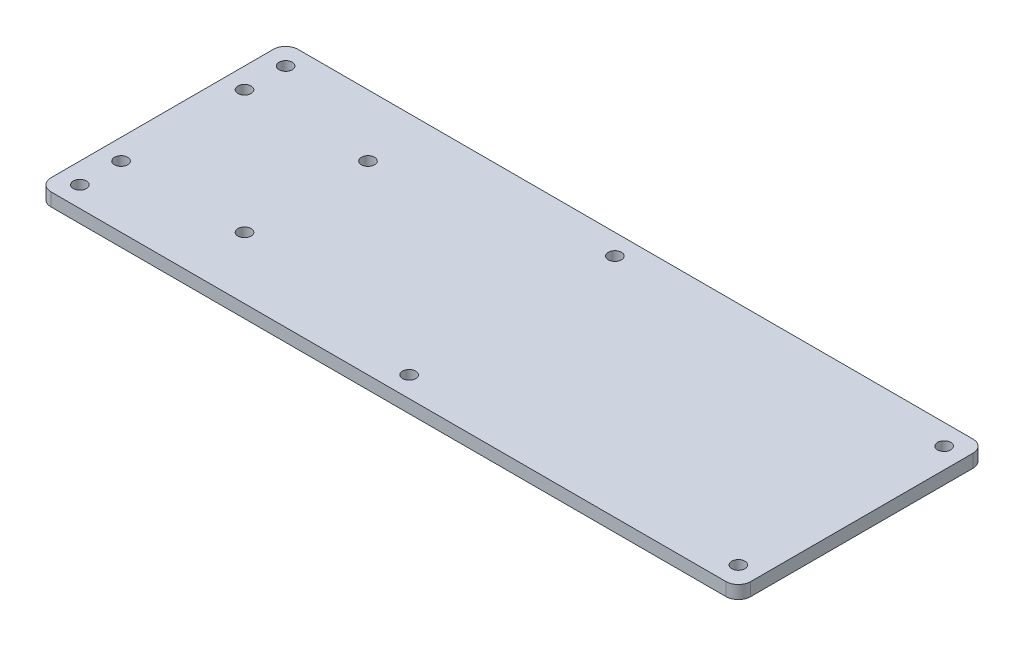
SolidWorks part; units mm, degrees
ref_plane "Front Plane" through (0, 0, 0) normal (0, 0, 1) x (1, 0, 0)
ref_plane "Top Plane" through (0, 0, 0) normal (0, 1, 0) x (1, 0, 0)
ref_plane "Right Plane" through (0, 0, 0) normal (1, 0, 0) x (0, 0, -1)
sketch "Sketch1" plane through (0, 0, 0) normal (0, 1, 0) x (1, 0, 0)
  line L1 (-85, 30) -> (85, 30)
  line L2 (-85, 30) -> (-85, -30)
  line L3 (-85, -30) -> (85, -30)
  line L4 (85, 30) -> (85, -30)
  line L5 (-85, 30) -> (85, -30) construction
  line L6 (-85, -30) -> (85, 30) construction
  point P0 (0, 0)
  dimension "D1" = 60
  dimension "D2" = 170
extrude "Boss-Extrude1" add sketch "Sketch1" along normal blind 3.175
sketch "Sketch2" plane through (0, 3.175, 0) normal (0, 1, 0) x (1, 0, 0)
  line L0 (0, 30) -> (0, -30) construction
  line L1 (-85, -30) -> (-80, -30) construction
  line L2 (-85, -30) -> (-85, -25) construction
  line L3 (-85, -25) -> (-80, -25) construction
  line L4 (-80, -30) -> (-80, -25) construction
  line L5 (-85, -30) -> (-80, -25) construction
  line L6 (-85, -25) -> (-80, -30) construction
  line L7 (85, 30) -> (-85, 30) construction
  line L8 (-85, -30) -> (85, -30) construction
  line L9 (-85, 0) -> (85, 0) construction
  line L10 (-85, 30) -> (-85, -30) construction
  line L11 (85, -30) -> (85, 30) construction
  circle A0 centre (-80, -25) radius 1.6
  circle A1 centre (-80, 25) radius 1.6
  circle A2 centre (80, 25) radius 1.6
  circle A3 centre (80, -25) radius 1.6
  circle A4 centre (0, -25) radius 1.6
  circle A5 centre (0, 25) radius 1.6
  point P4 (-82.5, -27.5)
  dimension "D2" = 3.2
  dimension "D1" = 5
  dimension "D3" = 5
extrude "Cut-Extrude1" cut sketch "Sketch2" against normal through all
sketch "Sketch3" plane through (0, 3.175, 0) normal (0, 1, 0) x (1, 0, 0)
  line L0 (-80, -23.4) -> (-80, 23.4) construction
  line L1 (-80, 0) -> (-85, 0) construction
  line L2 (-85, 30) -> (-85, -30) construction
  line L3 (-65, -30) -> (-65, 30) construction
  line L4 (-85, -30) -> (85, -30) construction
  line L5 (85, 30) -> (-85, 30) construction
  line L6 (-65, 0) -> (-80, 0) construction
  circle A0 centre (-80, -25) radius 1.6 construction
  circle A1 centre (-80, 25) radius 1.6 construction
  circle A2 centre (-80, -15) radius 1.6
  circle A3 centre (-80, 15) radius 1.6
  circle A4 centre (-50, 15) radius 1.6
  circle A5 centre (-50, -15) radius 1.6
  dimension "D1" = 15
  dimension "D2" = 15
extrude "Cut-Extrude2" cut sketch "Sketch3" against normal through all
fillet "Fillet1" radius 3 4 edges at (85, 1.5875, 30) (85, 1.5875, -30) (-85, 1.5875, -30) (-85, 1.5875, 30)
